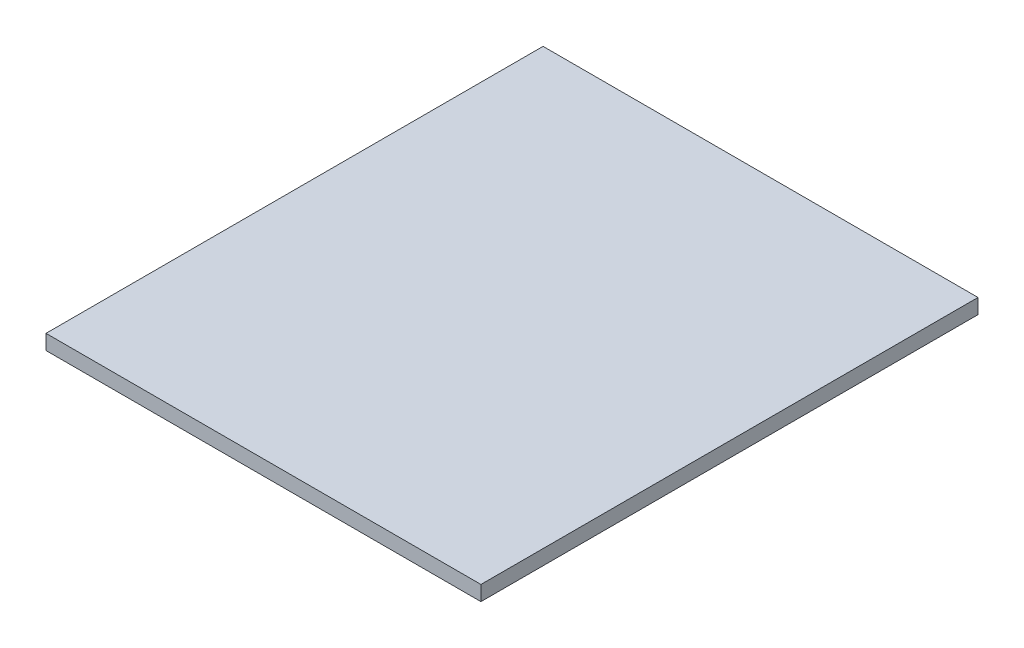
SolidWorks part; units mm, degrees
ref_plane "Plano frontal" through (0, 0, 0) normal (0, 0, 1) x (1, 0, 0)
ref_plane "Plano superior" through (0, 0, 0) normal (0, 1, 0) x (1, 0, 0)
ref_plane "Plano direito" through (0, 0, 0) normal (1, 0, 0) x (0, 0, -1)
sketch "Esboço1" plane through (0, 0, 0) normal (0, 1, 0) x (1, 0, 0)
  line L1 (-87.5, -100) -> (87.5, -100)
  line L2 (-87.5, -100) -> (-87.5, 100)
  line L3 (-87.5, 100) -> (87.5, 100)
  line L4 (87.5, -100) -> (87.5, 100)
  line L5 (-87.5, -100) -> (87.5, 100) construction
  line L6 (-87.5, 100) -> (87.5, -100) construction
  point P0 (0, 0)
  dimension "D1" = 200
  dimension "D2" = 175
extrude "Ressalto-extrusão1" add sketch "Esboço1" along normal blind 6
